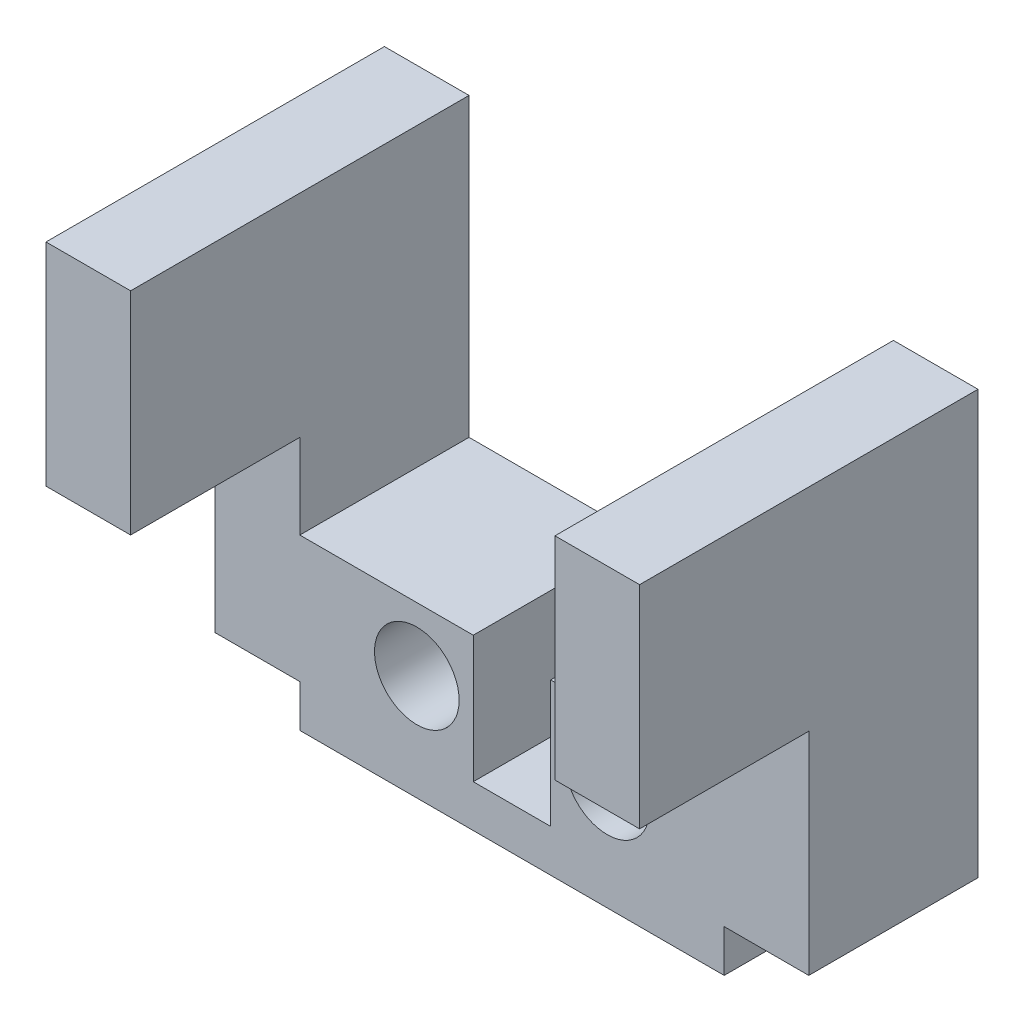
SolidWorks part; units mm, degrees
ref_plane "前视基准面" through (0, 0, 0) normal (0, 0, 1) x (1, 0, 0)
ref_plane "上视基准面" through (0, 0, 0) normal (0, 1, 0) x (1, 0, 0)
ref_plane "右视基准面" through (0, 0, 0) normal (1, 0, 0) x (0, 0, -1)
sketch "草图1" plane through (0, 0, 0) normal (0, 0, 1) x (1, 0, 0)
  line L0 (-9, 0) -> (9, 0) construction
  line L1 (0, 0) -> (0, 8.1604) construction
  line L2 (-1.8313, -3) -> (-1.8313, 3)
  line L3 (-1.8313, 3) -> (-10.0313, 3)
  line L10 (-10.0313, -3) -> (-14.0313, -3)
  line L11 (-14.0313, -3) -> (-14.0313, 17)
  line L12 (-10.0313, 3) -> (-10.0313, 17)
  line L13 (-10.0313, 17) -> (-14.0313, 17)
  line L14 (-10.0313, -3) -> (-10.0313, -5)
  line L15 (-10.0313, -5) -> (10.0313, -5)
  line L16 (10.0313, -5) -> (10.0313, -3)
  line L17 (-10.0313, 3) -> (-10.0313, -3) construction
  line L18 (10.0313, -3) -> (14.0313, -3)
  line L19 (14.0313, -3) -> (14.0313, 17)
  line L20 (10.0313, 17) -> (14.0313, 17)
  line L21 (10.0313, 3) -> (10.0313, 17)
  line L22 (1.8313, 3) -> (10.0313, 3)
  line L23 (1.8313, -3) -> (1.8313, 3)
  line L25 (1.8313, -3) -> (-1.8313, -3)
  circle A2 centre (-4.5, 0) radius 2
  circle A3 centre (4.5, 0) radius 2
  point P4 (0, 0)
  point P14 (-1.8313, 0)
  dimension "D7" = 4
  dimension "D8" = 1.8313
  dimension "D9" = 2.6687
  dimension "D1" = 8.2
  dimension "D3" = 6
  dimension "D4" = 4
  dimension "D5" = 20
  dimension "D6" = 2
extrude "凸台-拉伸1" add sketch "草图1" along normal blind 8
sketch "草图2" plane through (0, 0, 8) normal (0, 0, 1) x (1, 0, 0)
  line L0 (-10.0313, 3) -> (-10.0313, 17) construction
  line L1 (-14.0313, 17) -> (-10.0313, 17)
  line L2 (-14.0313, 17) -> (-14.0313, 7)
  line L3 (-14.0313, 7) -> (-10.0313, 7)
  line L4 (-10.0313, 17) -> (-10.0313, 7)
  line L5 (0, 0) -> (0, 13.6829) construction
  line L6 (14.0313, 7) -> (10.0313, 7)
  line L7 (10.0313, 17) -> (10.0313, 7)
  line L8 (14.0313, 17) -> (10.0313, 17)
  line L9 (14.0313, 17) -> (14.0313, 7)
  dimension "D1" = 10
extrude "凸台-拉伸2" add sketch "草图2" along normal blind 8
